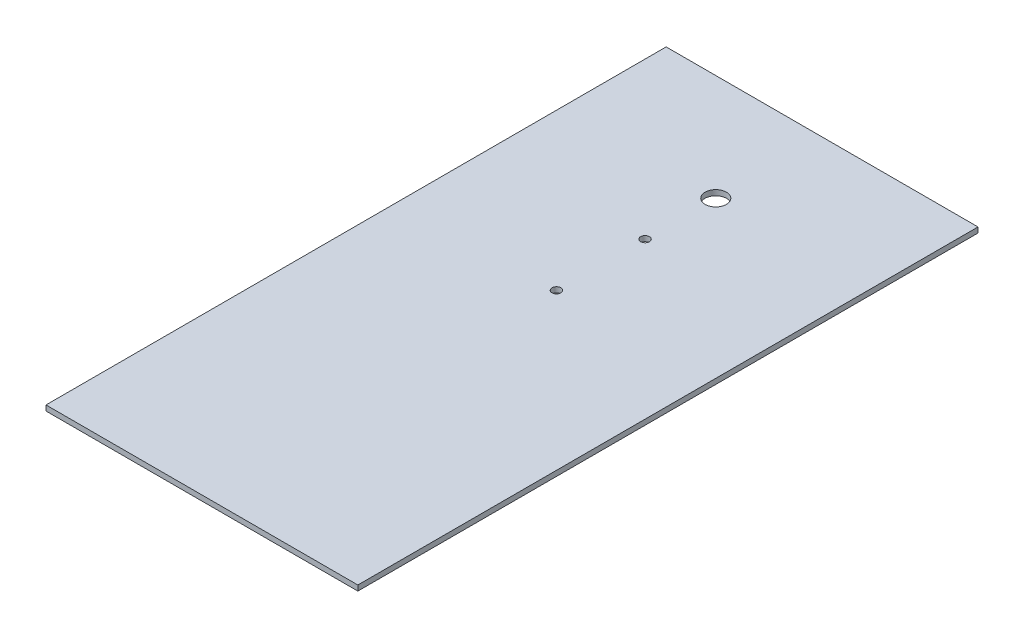
SolidWorks part; units mm, degrees
ref_plane "Front Plane" through (0, 0, 0) normal (0, 0, 1) x (1, 0, 0)
ref_plane "Top Plane" through (0, 0, 0) normal (0, 1, 0) x (1, 0, 0)
ref_plane "Right Plane" through (0, 0, 0) normal (1, 0, 0) x (0, 0, -1)
sketch "Sketch1" plane through (0, 0, 0) normal (0, 1, 0) x (1, 0, 0)
  line L1 (0, 0) -> (176, 0)
  line L2 (0, 0) -> (0, 350)
  line L3 (0, 350) -> (176, 350)
  line L4 (176, 0) -> (176, 350)
  dimension "D1" = 350
  dimension "D2" = 176
extrude "Boss-Extrude1" add sketch "Sketch1" along normal blind 3
hole_wizard "Ø5.0mm Dowel Hole1" positions "Sketch2" profile "Sketch3" hole size "Ø5.0" standard "ANSI Metric" end condition up to next
sketch "Sketch2" plane through (0, 0, 0) normal (0, -1, 0) x (-1, 0, 0)
  point P0 (-88.0169, 250.06)
  point P3 (-88.0169, 200.06)
sketch "Sketch3" plane through (88.0169, 0, -250.06) normal (1, 0, 0) x (0, 0, -1)
  line L0 (0, 0) -> (0, 3)
  line L1 (0, 3) -> (2.5, 3)
  line L2 (2.5, 3) -> (2.5, 0)
  line L5 (2.5, 0) -> (0, 0)
  line L11 (0, -6.35) -> (0, 107.95) construction
  dimension "Thru Hole Dia." = 5
  dimension "Thru Hole Depth" = 3
hole_wizard "Ø12.0mm Dowel Hole1" positions "Sketch6" profile "Sketch7" hole size "Ø12.0" standard "ANSI Metric" end condition up to next
sketch "Sketch6" plane through (0, 0, 0) normal (0, -1, 0) x (-1, 0, 0)
  point P0 (-88, 290)
sketch "Sketch7" plane through (88, 0, -290) normal (1, 0, 0) x (0, 0, -1)
  line L0 (0, 0) -> (0, 3)
  line L1 (0, 3) -> (6, 3)
  line L2 (6, 3) -> (6, 0)
  line L5 (6, 0) -> (0, 0)
  line L11 (0, -6.35) -> (0, 107.95) construction
  dimension "Thru Hole Dia." = 12
  dimension "Thru Hole Depth" = 3
